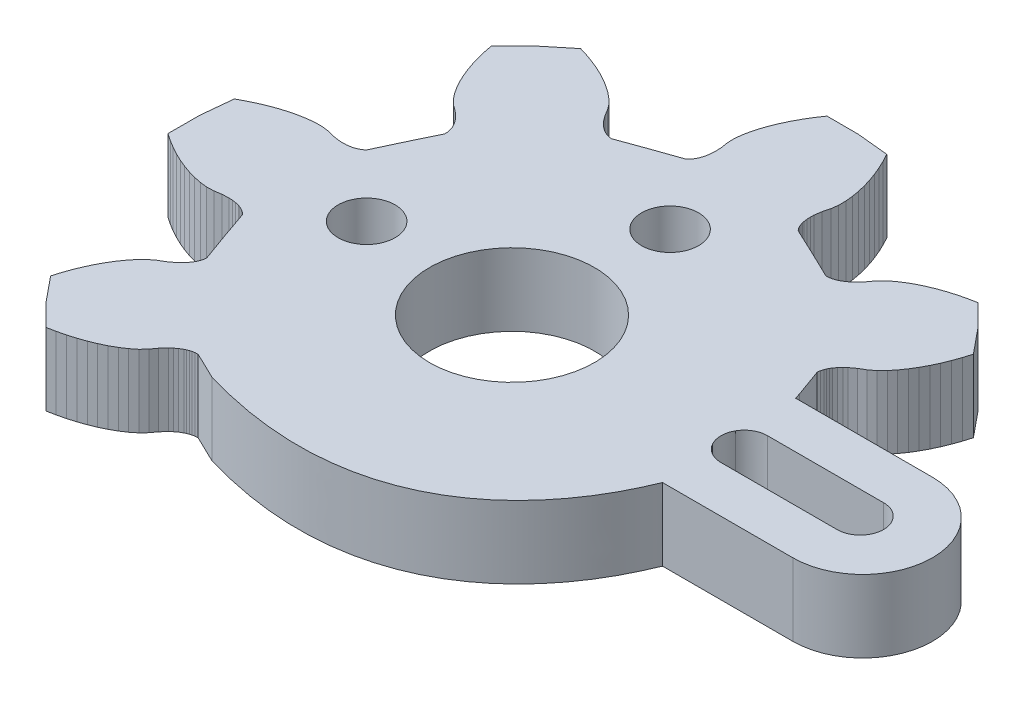
SolidWorks part; units mm, degrees
material "Acrylic (Medium-high impact)"
ref_plane "Front Plane" through (0, 0, 0) normal (0, 0, 1) x (1, 0, 0)
ref_plane "Top Plane" through (0, 0, 0) normal (0, 1, 0) x (1, 0, 0)
ref_plane "Right Plane" through (0, 0, 0) normal (1, 0, 0) x (0, 0, -1)
sketch "Sketch1" plane through (0, 0, 0) normal (0, 1, 0) x (1, 0, 0)
  line L0 (16.7784, -3.9694) -> (11.0716, -3.9694)
  line L1 (10.7786, 2.1509) -> (16.7784, 2.1509)
  line L2 (-6.5925, -0.5364) -> (-4.0925, -0.5364) construction
  line L3 (0.362, 5.814) -> (2.862, 5.814) construction
  line L4 (-2.098, -0.0119) -> (4.9058, -1.8066) construction
  line L5 (10.7786, 2.1509) -> (10.6999, 2.4044)
  line L6 (10.6999, 2.4044) -> (10.2639, 3.6122)
  line L7 (10.2639, 3.6122) -> (10.2809, 3.7455)
  line L8 (10.2809, 3.7455) -> (10.3115, 3.8519)
  line L9 (10.3115, 3.8519) -> (10.3488, 3.9436)
  line L10 (10.3488, 3.9436) -> (10.391, 4.0257)
  line L11 (10.391, 4.0257) -> (10.437, 4.1008)
  line L12 (10.437, 4.1008) -> (10.5372, 4.2349)
  line L13 (10.5372, 4.2349) -> (10.6458, 4.3533)
  line L14 (10.6458, 4.3533) -> (10.7612, 4.4596)
  line L15 (10.7612, 4.4596) -> (11.0078, 4.6435)
  line L16 (11.0078, 4.6435) -> (11.2721, 4.7969)
  line L17 (11.2721, 4.7969) -> (11.5173, 4.9833)
  line L18 (11.5173, 4.9833) -> (11.7382, 5.2106)
  line L19 (11.7382, 5.2106) -> (11.9436, 5.4628)
  line L20 (11.9436, 5.4628) -> (12.135, 5.736)
  line L21 (12.135, 5.736) -> (12.3129, 6.0278)
  line L22 (12.3129, 6.0278) -> (12.4778, 6.3364)
  line L23 (12.4778, 6.3364) -> (12.6295, 6.6611)
  line L24 (12.6295, 6.6611) -> (12.768, 7.0002)
  line L25 (12.768, 7.0002) -> (12.8927, 7.3535)
  line L26 (12.8927, 7.3535) -> (13.0042, 7.7198)
  line L27 (13.0042, 7.7198) -> (12.1265, 8.7922)
  line L28 (12.1265, 8.7922) -> (11.1504, 9.7759)
  line L29 (11.1504, 9.7759) -> (10.7755, 9.702)
  line L30 (10.7755, 9.702) -> (10.4122, 9.6135)
  line L31 (10.4122, 9.6135) -> (10.0613, 9.5099)
  line L32 (10.0613, 9.5099) -> (9.7237, 9.3918)
  line L33 (9.7237, 9.3918) -> (9.4002, 9.2586)
  line L34 (9.4002, 9.2586) -> (9.0925, 9.111)
  line L35 (9.0925, 9.111) -> (8.8018, 8.948)
  line L36 (8.8018, 8.948) -> (8.5304, 8.7691)
  line L37 (8.5304, 8.7691) -> (8.2823, 8.5717)
  line L38 (8.2823, 8.5717) -> (8.072, 8.3464)
  line L39 (8.072, 8.3464) -> (7.8929, 8.0986)
  line L40 (7.8929, 8.0986) -> (7.6854, 7.8715)
  line L41 (7.6854, 7.8715) -> (7.5682, 7.7671)
  line L42 (7.5682, 7.7671) -> (7.4396, 7.6709)
  line L43 (7.4396, 7.6709) -> (7.2962, 7.5848)
  line L44 (7.2962, 7.5848) -> (7.217, 7.5467)
  line L45 (7.217, 7.5467) -> (7.1312, 7.5127)
  line L46 (7.1312, 7.5127) -> (7.0363, 7.4848)
  line L47 (7.0363, 7.4848) -> (6.9276, 7.4654)
  line L48 (6.9276, 7.4654) -> (6.7932, 7.4618)
  line L49 (6.7932, 7.4618) -> (5.6382, 8.0189)
  line L50 (5.6382, 8.0189) -> (4.4775, 8.5641)
  line L51 (4.4775, 8.5641) -> (4.3956, 8.6706)
  line L52 (4.3956, 8.6706) -> (4.342, 8.7671)
  line L53 (4.342, 8.7671) -> (4.3036, 8.8586)
  line L54 (4.3036, 8.8586) -> (4.2756, 8.9466)
  line L55 (4.2756, 8.9466) -> (4.2551, 9.0322)
  line L56 (4.2551, 9.0322) -> (4.2312, 9.1981)
  line L57 (4.2312, 9.1981) -> (4.2245, 9.3586)
  line L58 (4.2245, 9.3586) -> (4.231, 9.5155)
  line L59 (4.231, 9.5155) -> (4.2758, 9.8203)
  line L60 (4.2758, 9.8203) -> (4.3543, 10.1161)
  line L61 (4.3543, 10.1161) -> (4.396, 10.4216)
  line L62 (4.396, 10.4216) -> (4.392, 10.7389)
  line L63 (4.392, 10.7389) -> (4.3591, 11.0628)
  line L64 (4.3591, 11.0628) -> (4.3014, 11.3914)
  line L65 (4.3014, 11.3914) -> (4.2214, 11.7238)
  line L66 (4.2214, 11.7238) -> (4.12, 12.059)
  line L67 (4.12, 12.059) -> (3.9983, 12.3959)
  line L68 (3.9983, 12.3959) -> (3.8567, 12.7337)
  line L69 (3.8567, 12.7337) -> (3.6958, 13.0719)
  line L70 (3.6958, 13.0719) -> (3.5161, 13.4096)
  line L71 (3.5161, 13.4096) -> (2.1384, 13.5463)
  line L72 (2.1384, 13.5463) -> (0.754, 13.5506)
  line L73 (0.754, 13.5506) -> (0.5407, 13.2329)
  line L74 (0.5407, 13.2329) -> (0.3464, 12.9126)
  line L75 (0.3464, 12.9126) -> (0.1713, 12.5908)
  line L76 (0.1713, 12.5908) -> (0.016, 12.2682)
  line L77 (0.016, 12.2682) -> (-0.1187, 11.9451)
  line L78 (-0.1187, 11.9451) -> (-0.2322, 11.6227)
  line L79 (-0.2322, 11.6227) -> (-0.3226, 11.3014)
  line L80 (-0.3226, 11.3014) -> (-0.3882, 10.9824)
  line L81 (-0.3882, 10.9824) -> (-0.4244, 10.6674)
  line L82 (-0.4244, 10.6674) -> (-0.4139, 10.3592)
  line L83 (-0.4139, 10.3592) -> (-0.3657, 10.0572)
  line L84 (-0.3657, 10.0572) -> (-0.3522, 9.7492)
  line L85 (-0.3522, 9.7492) -> (-0.3614, 9.5925)
  line L86 (-0.3614, 9.5925) -> (-0.3844, 9.4334)
  line L87 (-0.3844, 9.4334) -> (-0.4247, 9.2708)
  line L88 (-0.4247, 9.2708) -> (-0.4539, 9.1879)
  line L89 (-0.4539, 9.1879) -> (-0.4909, 9.1032)
  line L90 (-0.4909, 9.1032) -> (-0.5383, 9.016)
  line L91 (-0.5383, 9.016) -> (-0.6013, 8.9254)
  line L92 (-0.6013, 8.9254) -> (-0.6937, 8.8277)
  line L93 (-0.6937, 8.8277) -> (-1.9036, 8.4036)
  line L94 (-1.9036, 8.4036) -> (-3.1092, 7.9667)
  line L95 (-3.1092, 7.9667) -> (-3.2423, 7.9839)
  line L96 (-3.2423, 7.9839) -> (-3.3485, 8.0142)
  line L97 (-3.3485, 8.0142) -> (-3.4401, 8.0518)
  line L98 (-3.4401, 8.0518) -> (-3.5219, 8.0943)
  line L99 (-3.5219, 8.0943) -> (-3.5969, 8.1401)
  line L100 (-3.5969, 8.1401) -> (-3.731, 8.2406)
  line L101 (-3.731, 8.2406) -> (-3.849, 8.3493)
  line L102 (-3.849, 8.3493) -> (-3.9552, 8.4649)
  line L103 (-3.9552, 8.4649) -> (-4.1386, 8.7122)
  line L104 (-4.1386, 8.7122) -> (-4.2918, 8.9769)
  line L105 (-4.2918, 8.9769) -> (-4.478, 9.2225)
  line L106 (-4.478, 9.2225) -> (-4.7047, 9.4438)
  line L107 (-4.7047, 9.4438) -> (-4.9566, 9.6496)
  line L108 (-4.9566, 9.6496) -> (-5.2292, 9.8412)
  line L109 (-5.2292, 9.8412) -> (-5.5206, 10.0196)
  line L110 (-5.5206, 10.0196) -> (-5.8288, 10.1844)
  line L111 (-5.8288, 10.1844) -> (-6.1526, 10.3367)
  line L112 (-6.1526, 10.3367) -> (-6.4913, 10.4753)
  line L113 (-6.4913, 10.4753) -> (-6.8436, 10.6005)
  line L114 (-6.8436, 10.6005) -> (-7.2094, 10.7119)
  line L115 (-7.2094, 10.7119) -> (-8.28, 9.8327)
  line L116 (-8.28, 9.8327) -> (-9.2618, 8.8548)
  line L117 (-9.2618, 8.8548) -> (-9.1883, 8.4792)
  line L118 (-9.1883, 8.4792) -> (-9.0999, 8.1153)
  line L119 (-9.0999, 8.1153) -> (-8.9963, 7.7639)
  line L120 (-8.9963, 7.7639) -> (-8.8784, 7.4255)
  line L121 (-8.8784, 7.4255) -> (-8.7457, 7.1014)
  line L122 (-8.7457, 7.1014) -> (-8.5982, 6.7932)
  line L123 (-8.5982, 6.7932) -> (-8.4356, 6.502)
  line L124 (-8.4356, 6.502) -> (-8.2568, 6.2301)
  line L125 (-8.2568, 6.2301) -> (-8.06, 5.9815)
  line L126 (-8.06, 5.9815) -> (-7.8349, 5.771)
  line L127 (-7.8349, 5.771) -> (-7.5877, 5.5915)
  line L128 (-7.5877, 5.5915) -> (-7.3607, 5.3835)
  line L129 (-7.3607, 5.3835) -> (-7.2568, 5.2661)
  line L130 (-7.2568, 5.2661) -> (-7.1608, 5.1373)
  line L131 (-7.1608, 5.1373) -> (-7.0746, 4.9936)
  line L132 (-7.0746, 4.9936) -> (-7.0366, 4.9143)
  line L133 (-7.0366, 4.9143) -> (-7.0029, 4.8283)
  line L134 (-7.0029, 4.8283) -> (-6.9749, 4.7332)
  line L135 (-6.9749, 4.7332) -> (-6.9556, 4.6242)
  line L136 (-6.9556, 4.6242) -> (-6.9522, 4.4899)
  line L137 (-6.9522, 4.4899) -> (-7.5082, 3.3328)
  line L138 (-7.5082, 3.3328) -> (-8.0522, 2.17)
  line L139 (-8.0522, 2.17) -> (-8.1585, 2.0878)
  line L140 (-8.1585, 2.0878) -> (-8.2551, 2.0341)
  line L141 (-8.2551, 2.0341) -> (-8.3464, 1.9959)
  line L142 (-8.3464, 1.9959) -> (-8.4341, 1.9675)
  line L143 (-8.4341, 1.9675) -> (-8.5196, 1.947)
  line L144 (-8.5196, 1.947) -> (-8.6852, 1.9231)
  line L145 (-8.6852, 1.9231) -> (-8.8456, 1.9164)
  line L146 (-8.8456, 1.9164) -> (-9.0019, 1.9229)
  line L147 (-9.0019, 1.9229) -> (-9.3063, 1.9677)
  line L148 (-9.3063, 1.9677) -> (-9.6014, 2.0464)
  line L149 (-9.6014, 2.0464) -> (-9.9063, 2.0883)
  line L150 (-9.9063, 2.0883) -> (-10.2231, 2.0842)
  line L151 (-10.2231, 2.0842) -> (-10.5464, 2.0513)
  line L152 (-10.5464, 2.0513) -> (-10.8743, 1.9937)
  line L153 (-10.8743, 1.9937) -> (-11.2061, 1.9133)
  line L154 (-11.2061, 1.9133) -> (-11.5408, 1.8116)
  line L155 (-11.5408, 1.8116) -> (-11.8769, 1.6899)
  line L156 (-11.8769, 1.6899) -> (-12.2143, 1.5479)
  line L157 (-12.2143, 1.5479) -> (-12.5519, 1.3868)
  line L158 (-12.5519, 1.3868) -> (-12.8891, 1.2066)
  line L159 (-12.8891, 1.2066) -> (-13.0256, -0.1735)
  line L160 (-13.0256, -0.1735) -> (-13.0296, -1.5604)
  line L161 (-13.0296, -1.5604) -> (-12.7125, -1.7739)
  line L162 (-12.7125, -1.7739) -> (-12.3929, -1.9686)
  line L163 (-12.3929, -1.9686) -> (-12.0718, -2.144)
  line L164 (-12.0718, -2.144) -> (-11.7496, -2.2997)
  line L165 (-11.7496, -2.2997) -> (-11.4271, -2.4347)
  line L166 (-11.4271, -2.4347) -> (-11.1052, -2.5483)
  line L167 (-11.1052, -2.5483) -> (-10.7847, -2.639)
  line L168 (-10.7847, -2.639) -> (-10.4663, -2.7046)
  line L169 (-10.4663, -2.7046) -> (-10.1517, -2.7409)
  line L170 (-10.1517, -2.7409) -> (-9.844, -2.7302)
  line L171 (-9.844, -2.7302) -> (-9.5425, -2.6822)
  line L172 (-9.5425, -2.6822) -> (-9.2354, -2.6685)
  line L173 (-9.2354, -2.6685) -> (-9.0789, -2.6778)
  line L174 (-9.0789, -2.6778) -> (-8.9199, -2.7009)
  line L175 (-8.9199, -2.7009) -> (-8.7578, -2.7415)
  line L176 (-8.7578, -2.7415) -> (-8.6749, -2.7705)
  line L177 (-8.6749, -2.7705) -> (-8.5903, -2.8074)
  line L178 (-8.5903, -2.8074) -> (-8.5033, -2.8549)
  line L179 (-8.5033, -2.8549) -> (-8.413, -2.9182)
  line L180 (-8.413, -2.9182) -> (-8.3156, -3.0107)
  line L181 (-8.3156, -3.0107) -> (-7.8919, -4.2231)
  line L182 (-7.8919, -4.2231) -> (-7.456, -5.4305)
  line L183 (-7.456, -5.4305) -> (-7.4732, -5.564)
  line L184 (-7.4732, -5.564) -> (-7.5033, -5.6703)
  line L185 (-7.5033, -5.6703) -> (-7.5408, -5.7621)
  line L186 (-7.5408, -5.7621) -> (-7.5831, -5.8443)
  line L187 (-7.5831, -5.8443) -> (-7.6291, -5.9191)
  line L188 (-7.6291, -5.9191) -> (-7.7293, -6.0535)
  line L189 (-7.7293, -6.0535) -> (-7.838, -6.1717)
  line L190 (-7.838, -6.1717) -> (-7.9533, -6.2781)
  line L191 (-7.9533, -6.2781) -> (-8.2, -6.4617)
  line L192 (-8.2, -6.4617) -> (-8.4642, -6.6154)
  line L193 (-8.4642, -6.6154) -> (-8.7094, -6.8017)
  line L194 (-8.7094, -6.8017) -> (-8.9304, -7.029)
  line L195 (-8.9304, -7.029) -> (-9.136, -7.2812)
  line L196 (-9.136, -7.2812) -> (-9.327, -7.5546)
  line L197 (-9.327, -7.5546) -> (-9.505, -7.8464)
  line L198 (-9.505, -7.8464) -> (-9.6698, -8.155)
  line L199 (-9.6698, -8.155) -> (-9.8216, -8.4796)
  line L200 (-9.8216, -8.4796) -> (-9.9599, -8.8186)
  line L201 (-9.9599, -8.8186) -> (-10.0849, -9.1719)
  line L202 (-10.0849, -9.1719) -> (-10.1961, -9.5382)
  line L203 (-10.1961, -9.5382) -> (-9.3187, -10.6106)
  line L204 (-9.3187, -10.6106) -> (-8.3425, -11.5942)
  line L205 (-8.3425, -11.5942) -> (-7.9674, -11.5205)
  line L206 (-7.9674, -11.5205) -> (-7.6042, -11.4318)
  line L207 (-7.6042, -11.4318) -> (-7.2532, -11.3284)
  line L208 (-7.2532, -11.3284) -> (-6.9156, -11.2102)
  line L209 (-6.9156, -11.2102) -> (-6.5924, -11.0773)
  line L210 (-6.5924, -11.0773) -> (-6.2845, -10.9296)
  line L211 (-6.2845, -10.9296) -> (-5.9938, -10.7667)
  line L212 (-5.9938, -10.7667) -> (-5.7223, -10.5874)
  line L213 (-5.7223, -10.5874) -> (-5.4744, -10.3902)
  line L214 (-5.4744, -10.3902) -> (-5.2642, -10.165)
  line L215 (-5.2642, -10.165) -> (-5.085, -9.9172)
  line L216 (-5.085, -9.9172) -> (-4.8775, -9.6899)
  line L217 (-4.8775, -9.6899) -> (-4.7602, -9.5858)
  line L218 (-4.7602, -9.5858) -> (-4.6315, -9.4896)
  line L219 (-4.6315, -9.4896) -> (-4.4881, -9.4032)
  line L220 (-4.4881, -9.4032) -> (-4.409, -9.3651)
  line L221 (-4.409, -9.3651) -> (-4.3232, -9.3312)
  line L222 (-4.3232, -9.3312) -> (-4.2282, -9.3034)
  line L223 (-4.2282, -9.3034) -> (-4.1196, -9.2838)
  line L224 (-4.1196, -9.2838) -> (-3.9854, -9.2804)
  line L225 (-3.9854, -9.2804) -> (-2.8303, -9.8374)
  line L226 (11.5859, -1.9292) -> (16.6769, -1.9292)
  line L227 (16.6769, 0.1108) -> (11.5859, 0.1108)
  arc A0 (16.7784, 2.1509) -> (16.7784, -3.9694) centre (16.7784, -0.9092) cw
  circle A1 centre (-5.3425, -0.5364) radius 1.25
  circle A2 centre (1.612, 5.814) radius 1.25
  circle A3 centre (1.4039, -0.9092) radius 3.615
  spline S4 degree 3 poles (-2.8303, -9.8374) (8.2625, -13.145) (10.954, -3.9694) (11.0716, -3.9694) knots 226 226 226 226 227 227 227 227
  spline S10 degree 3 poles (11.5859, 0.1108) (11.2221, 0.1108) (10.886, -0.0835) (10.704, -0.3993) knots 0 0 0 0 1 1 1 1
  spline S11 degree 3 poles (10.704, -0.3993) (10.5221, -0.7149) (10.5221, -1.1036) (10.704, -1.4192) knots 1 1 1 1 2 2 2 2
  spline S12 degree 3 poles (10.704, -1.4192) (10.886, -1.7349) (11.2221, -1.9292) (11.5859, -1.9292) knots 2 2 2 2 3 3 3 3
  spline S13 degree 3 poles (16.6769, -1.9292) (17.239, -1.9292) (17.6949, -1.4724) (17.6949, -0.9093) knots 4 4 4 4 5 5 5 5
  spline S14 degree 3 poles (17.6949, -0.9093) (17.6949, -0.3459) (17.239, 0.1108) (16.6769, 0.1108) knots 5 5 5 5 6 6 6 6
  dimension "D1" = 2.5
extrude "Boss-Extrude1" add sketch "Sketch1" along normal blind 3.175
